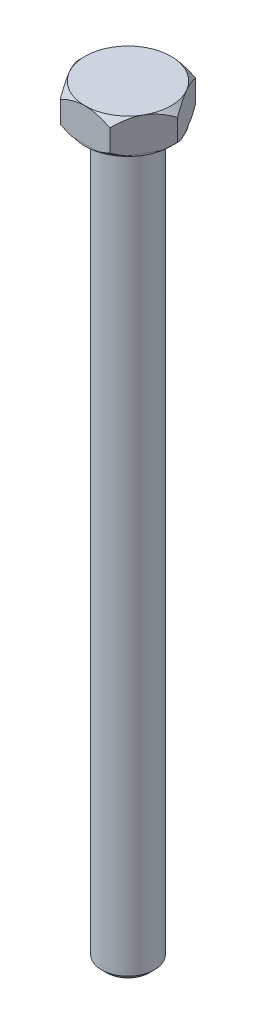
SolidWorks part; units mm, degrees
material "Cast Stainless Steel"
ref_plane "Front Plane" through (0, 0, 0) normal (0, 0, 1) x (1, 0, 0)
ref_plane "Top Plane" through (0, 0, 0) normal (0, 1, 0) x (1, 0, 0)
ref_plane "Right Plane" through (0, 0, 0) normal (1, 0, 0) x (0, 0, -1)
sketch "Sketch1" plane through (0, 0, 0) normal (0, 1, 0) x (1, 0, 0)
  line L0 (0, 0) -> (7.5056, 0) construction
  line L1 (7.5056, 0) -> (3.7528, 6.5)
  line L2 (3.7528, 6.5) -> (-3.7528, 6.5)
  line L3 (-3.7528, 6.5) -> (-7.5056, 0)
  line L4 (-7.5056, 0) -> (-3.7528, -6.5)
  line L5 (-3.7528, -6.5) -> (3.7528, -6.5)
  line L6 (3.7528, -6.5) -> (7.5056, 0)
  circle A0 centre (0, 0) radius 6.5 construction
  dimension "D1" = 13
extrude "Boss-Extrude1" add sketch "Sketch1" against normal blind 5.3
sketch "Sketch4" plane through (0, 0, 0) normal (1, 0, 0) x (0, 0, -1)
  line L0 (-6.5, 0) -> (-8.15, 0)
  line L1 (-8.15, 0) -> (-8.15, -1.65)
  line L2 (-8.15, -1.65) -> (-6.5, 0)
  line L3 (-6.5, -2.65) -> (6.5, -2.65) construction
  line L4 (-8.15, -3.65) -> (-6.5, -5.3)
  line L5 (-8.15, -5.3) -> (-8.15, -3.65)
  line L6 (-6.5, -5.3) -> (-8.15, -5.3)
  line L7 (0, 0) -> (0, -2.65) construction
  dimension "D1" = 45
  dimension "D2" = 2.65
  dimension "D3" = 1.65
  dimension "D4" = 13
revolve "Cut-Revolve1" cut sketch "Sketch4" angle 360 about L7
sketch "Sketch2" plane through (0, -5.3, 0) normal (0, -1, 0) x (1, 0, 0)
  circle A0 centre (0, 0) radius 6.5
  dimension "D1" = 13
extrude "Cut-Extrude1" cut sketch "Sketch2" against normal blind 0.265 flip side to cut
sketch "Sketch3" plane through (0, -5.3, 0) normal (0, -1, 0) x (1, 0, 0)
  circle A0 centre (0, 0) radius 4
  dimension "D1" = 8
extrude "Boss-Extrude2" add sketch "Sketch3" along normal blind 110
chamfer "Chamfer1" distance 0.8 angle 45 1 edges at (0, -115.3, -4)
equation "\"k\"= 5.3"
equation "\"e\"= 14.38"
equation "\"S\"= 13"
equation "\"L\"=110"
equation "\"D1@Sketch1\"=\"S\""
equation "\"D1@Boss-Extrude1\"=\"k\""
equation "\"D1@Sketch2\"=\"S\""
equation "\"D1@Cut-Extrude1\"=\"k\"/20"
equation "\"d\"= 8"
equation "\"D1@Sketch3\"=\"d\""
equation "\"D1@Boss-Extrude2\"=\"L\""
equation "\"D2@Sketch4\"=\"k\"/2"
equation "\"D3@Sketch4\"=\"D2@Sketch4\"-1"
equation "\"D4@Sketch4\"=\"S\""
equation "\"D1@Chamfer1\"=\"d\"/10"
